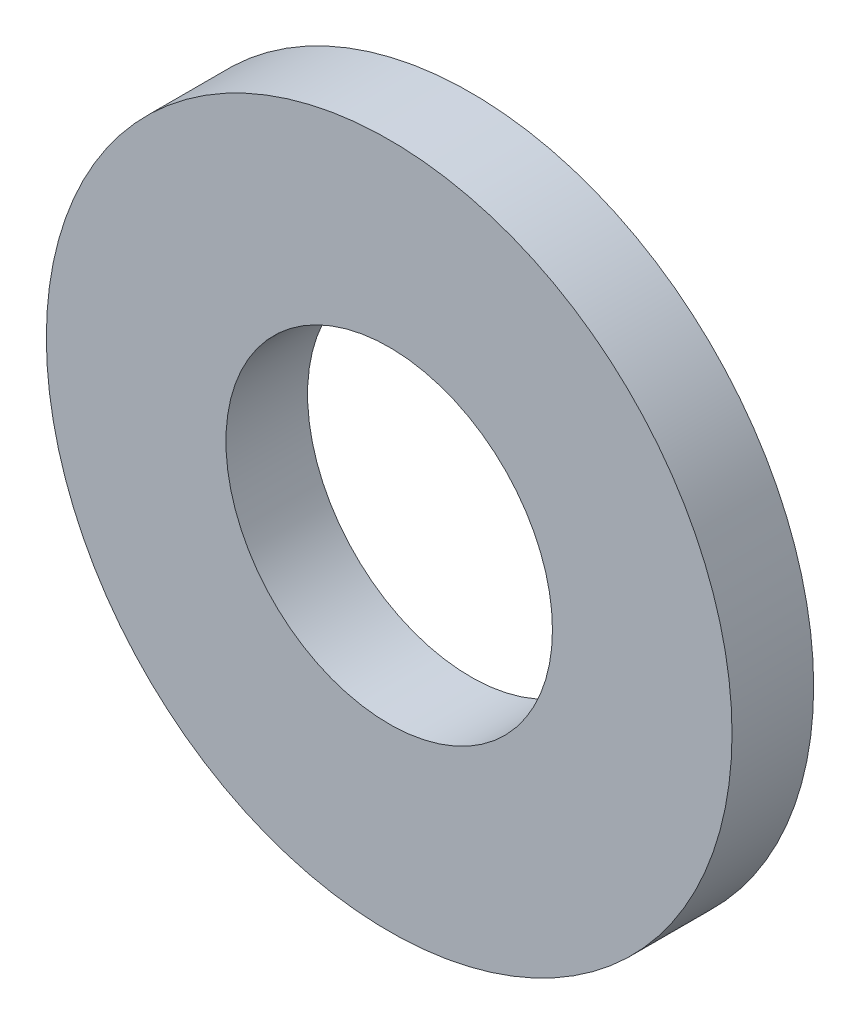
SolidWorks part; units mm, degrees
material "PLA"
ref_plane "Front Plane" through (0, 0, 0) normal (0, 0, 1) x (1, 0, 0)
ref_plane "Top Plane" through (0, 0, 0) normal (0, 1, 0) x (1, 0, 0)
ref_plane "Right Plane" through (0, 0, 0) normal (1, 0, 0) x (0, 0, -1)
sketch "Sketch1" plane through (0, 0, 0) normal (0, 0, 1) x (1, 0, 0)
  circle A0 centre (0, 0) radius 10.5
  circle A1 centre (0, 0) radius 5
  dimension "D1" = 21
  dimension "D2" = 10
extrude "Boss-Extrude1" add sketch "Sketch1" along normal blind 2.5
